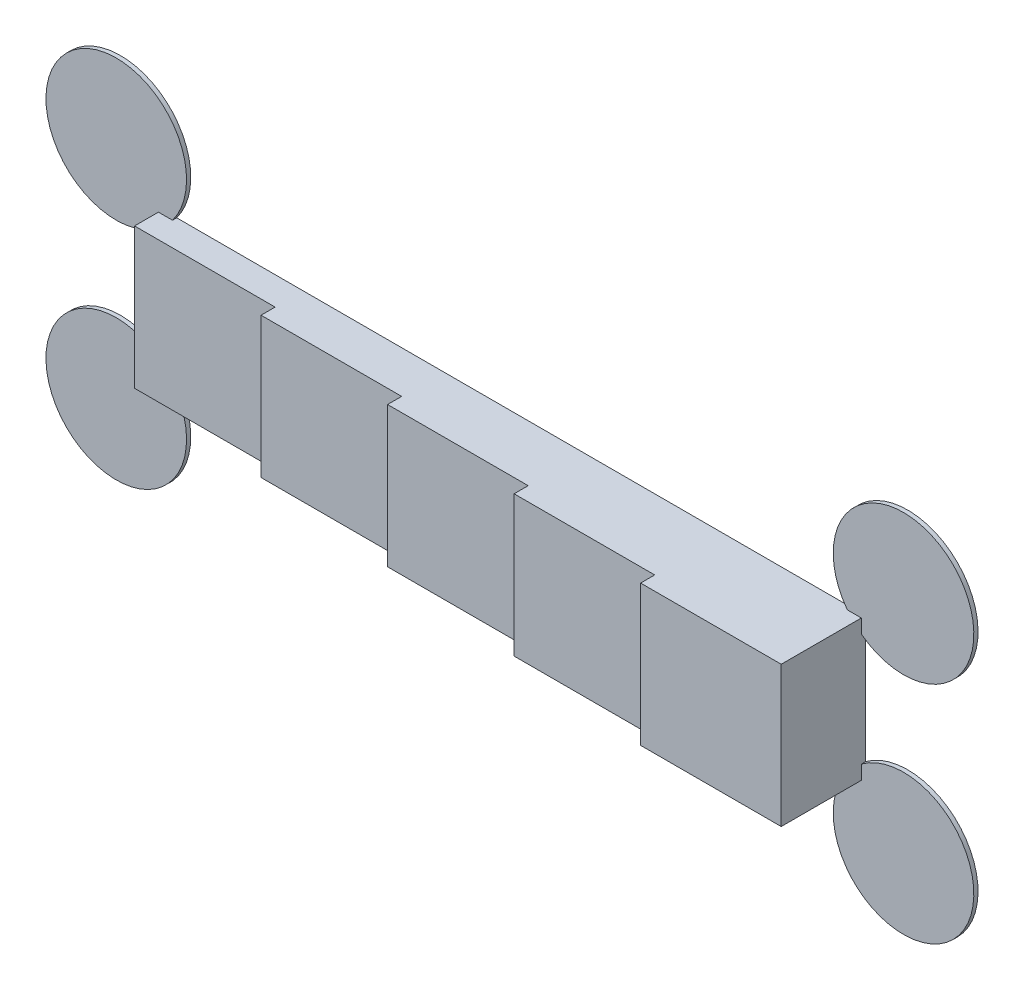
SolidWorks part; units mm, degrees
ref_plane "Front Plane" through (0, 0, 0) normal (0, 0, 1) x (1, 0, 0)
ref_plane "Top Plane" through (0, 0, 0) normal (0, 1, 0) x (1, 0, 0)
ref_plane "Right Plane" through (0, 0, 0) normal (1, 0, 0) x (0, 0, -1)
sketch "Sketch1" plane through (0, 0, 0) normal (0, 0, 1) x (1, 0, 0)
  line L1 (0, 0) -> (50, 0)
  line L2 (0, 0) -> (0, 10)
  line L3 (0, 10) -> (50, 10)
  line L4 (50, 0) -> (50, 10)
  dimension "D1" = 10
  dimension "D2" = 50
extrude "2mm" add sketch "Sketch1" along normal blind 2
sketch "Sketch2" plane through (0, 0, 2) normal (0, 0, 1) x (1, 0, 0)
  line L0 (0, 0) -> (50, 0) construction
  line L1 (50, 10) -> (10, 10)
  line L2 (50, 10) -> (50, 0)
  line L3 (50, 0) -> (10, 0)
  line L4 (10, 10) -> (10, 0)
  dimension "D1" = 40
extrude "3mm" add sketch "Sketch2" along normal blind 1
sketch "Sketch3" plane through (0, 0, 3) normal (0, 0, 1) x (1, 0, 0)
  line L0 (10, 0) -> (50, 0) construction
  line L1 (50, 10) -> (20, 10)
  line L2 (50, 10) -> (50, 0)
  line L3 (50, 0) -> (20, 0)
  line L4 (20, 10) -> (20, 0)
  dimension "D1" = 30
extrude "4mm" add sketch "Sketch3" along normal blind 1
sketch "Sketch4" plane through (0, 0, 4) normal (0, 0, 1) x (1, 0, 0)
  line L0 (20, 0) -> (50, 0) construction
  line L1 (50, 10) -> (30, 10)
  line L2 (50, 10) -> (50, 0)
  line L3 (50, 0) -> (30, 0)
  line L4 (30, 10) -> (30, 0)
  dimension "D1" = 20
extrude "5mm" add sketch "Sketch4" along normal blind 1
sketch "Sketch5" plane through (0, 0, 5) normal (0, 0, 1) x (1, 0, 0)
  line L0 (50, 10) -> (30, 10) construction
  line L1 (40, 10) -> (50, 10)
  line L2 (40, 10) -> (40, 0)
  line L3 (40, 0) -> (50, 0)
  line L4 (50, 10) -> (50, 0)
extrude "6mm" add sketch "Sketch5" along normal blind 1
sketch "Sketch6" plane through (0, 0, 0) normal (0, 0, -1) x (-1, 0, 0)
  line L0 (0, 0) -> (-50, 0) construction
  line L1 (0, 10) -> (0, 0) construction
  circle A0 centre (3, -3) radius 5
  circle A1 centre (3, 13) radius 5
  circle A2 centre (-53, 13) radius 5
  circle A3 centre (-53, -3) radius 5
  dimension "D1" = 10
  dimension "D2" = 3
  dimension "D3" = 3
  dimension "D4" = 2
  dimension "D5" = 2
extrude "Print ears" add sketch "Sketch6" against normal blind 0.3
